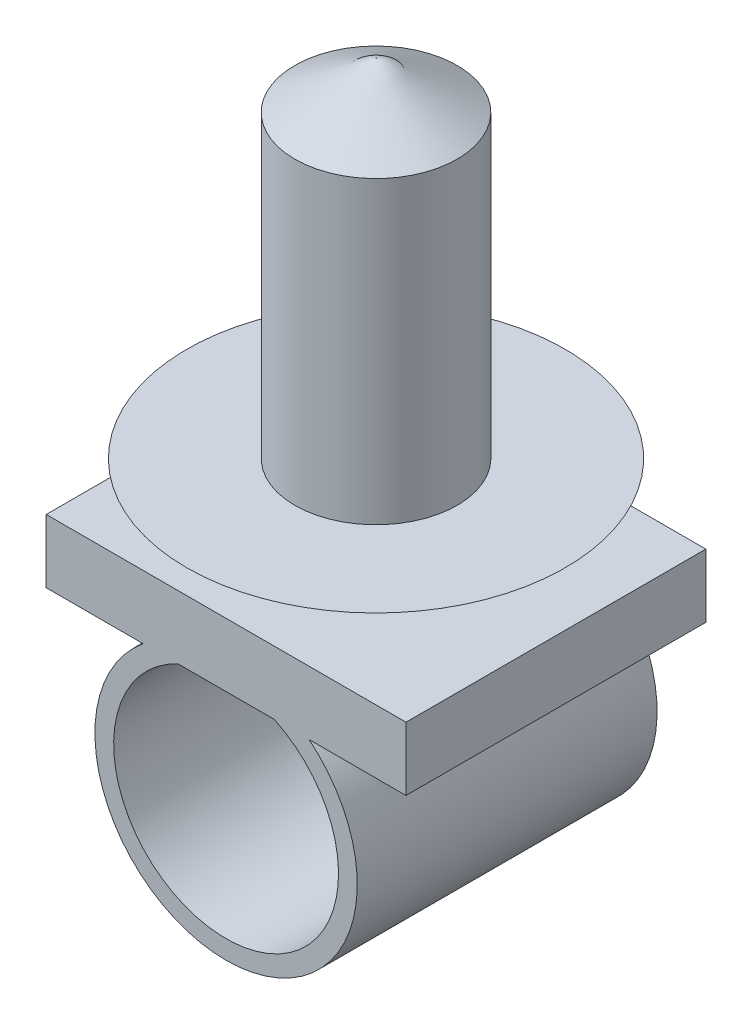
SolidWorks part; units mm, degrees
ref_plane "Front Plane" through (0, 0, 0) normal (0, 0, 1) x (1, 0, 0)
ref_plane "Top Plane" through (0, 0, 0) normal (0, 1, 0) x (1, 0, 0)
ref_plane "Right Plane" through (0, 0, 0) normal (1, 0, 0) x (0, 0, -1)
sketch "Sketch1" plane through (0, 0, 0) normal (0, 0, 1) x (1, 0, 0)
  circle A0 centre (0, 0) radius 4.5
  circle A1 centre (0, 0) radius 5.25
  dimension "D1" = 9
  dimension "D2" = 10.5
extrude "Boss-Extrude1" add sketch "Sketch1" along normal blind 12
ref_plane "Plane1" through (0, 4.064, 0) normal (0, 1, 0) x (1, 0, 0)
sketch "Sketch2" plane through (0, 4.064, 0) normal (0, 1, 0) x (1, 0, 0)
  line L0 (0, 0) -> (7.2, 0)
  line L1 (5.25, 0) -> (-5.25, 0) construction
  line L2 (7.2, 0) -> (7.2, -12)
  line L3 (-5.25, -12) -> (5.25, -12) construction
  line L4 (7.2, -12) -> (-7.2, -12)
  line L5 (-7.2, -12) -> (-7.2, 0)
  line L6 (4.5, 0) -> (-4.5, 0) construction
  line L7 (-7.2, 0) -> (0, 0)
  dimension "D1" = 7.2
  dimension "D2" = 7.2
extrude "Boss-Extrude2" add sketch "Sketch2" along normal blind 2.54
sketch "Sketch3" plane through (0, 6.604, 0) normal (0, 1, 0) x (1, 0, 0)
  line L0 (-7.2, 0) -> (7.2, -12) construction
  circle A0 centre (0, -6) radius 3.175
  dimension "D1" = 6.35
extrude "Boss-Extrude3" add sketch "Sketch3" along normal blind 2.54 draft 60 draft outward yes
sketch "Sketch4" plane through (0, 9.144, 0) normal (0, 1, 0) x (1, 0, 0)
  circle A0 centre (0, -6) radius 3.25
extrude "Boss-Extrude4" add sketch "Sketch4" along normal blind 12
sketch "Sketch5" plane through (0, 21.144, 0) normal (0, 1, 0) x (1, 0, 0)
  circle A0 centre (0, -6) radius 3.25
extrude "Boss-Extrude5" add sketch "Sketch5" along normal blind 3.05 draft 60
